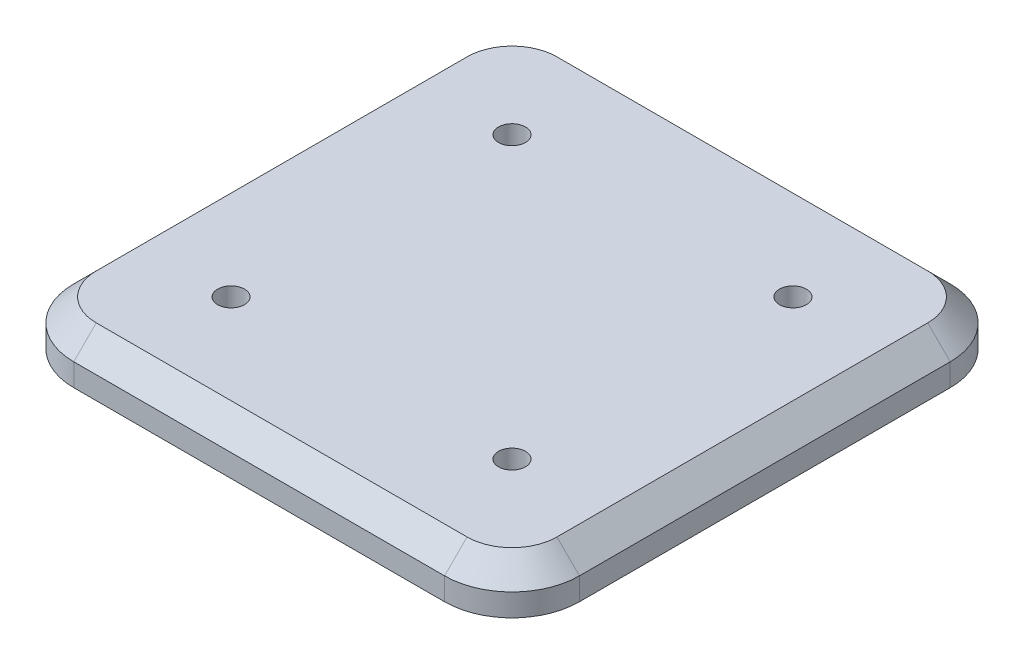
SolidWorks part; units mm, degrees
ref_plane "前基準面" through (0, 0, 0) normal (0, 0, 1) x (1, 0, 0)
ref_plane "上基準面" through (0, 0, 0) normal (0, 1, 0) x (1, 0, 0)
ref_plane "右基準面" through (0, 0, 0) normal (1, 0, 0) x (0, 0, -1)
ref_plane "平面1"
sketch "草圖1" plane through (0, 0, 0) normal (0, 1, 0) x (-1, 0, 0)
  line L0 (112.5, -112.5) -> (-112.5, -112.5)
  line L1 (-112.5, -112.5) -> (-112.5, 112.5)
  line L2 (-112.5, 112.5) -> (112.5, 112.5)
  line L3 (112.5, 112.5) -> (112.5, -112.5)
  dimension "D1" = 225
  dimension "D2" = 225
extrude "擠出1" add sketch "草圖1" along normal blind 20
fillet "圓角1" radius 30 4 edges at (-112.5, 10, 112.5) (-112.5, 10, -112.5) (112.5, 10, -112.5) (112.5, 10, 112.5)
chamfer "倒角1" distance 10 distance2 10 8 edges at (103.7132, 20, 103.7132) (0, 20, 112.5) (-103.7132, 20, 103.7132) (-112.5, 20, 0) (-103.7132, 20, -103.7132) (0, 20, -112.5) (103.7132, 20, -103.7132) (112.5, 20, 0)
hole_wizard "孔1" positions "草圖3" profile "草圖2" legacy
sketch "草圖3" plane through (0, 0, 0) normal (0, -1, 0) x (-1, 0, 0)
  point P1 (-87.5, 87.5)
  point P2 (-87.5, -87.5)
  point P3 (87.5, -87.5)
  point P4 (87.5, 87.5)
sketch "草圖2" plane through (87.5, 0, -87.5) normal (1, 0, 0) x (0, 0, -1)
  line L0 (0, 0) -> (0, 13.6052)
  line L1 (0, 13.6052) -> (6, 10)
  line L2 (6, 10) -> (6, 0)
  line L4 (6, 0) -> (0, 0)
  line L6 (0, 13.6052) -> (-6, 10) construction
  line L7 (0, -4.2442) -> (0, 117.3081) construction
  dimension "直徑" = 12
  dimension "深度" = 10
  dimension "導頭角度" = 118
hole_wizard "孔2" positions "草圖5" profile "草圖4" legacy
sketch "草圖5" plane through (0, 20, 0) normal (0, 1, 0) x (1, 0, 0)
  point P1 (-62.5, 62.5)
  point P2 (62.5, 62.5)
  point P3 (62.5, -62.5)
  point P4 (-62.5, -62.5)
sketch "草圖4" plane through (-62.5, 20, -62.5) normal (1, 0, 0) x (0, 0, 1)
  line L0 (0, 0) -> (0, 13.6052)
  line L1 (0, 13.6052) -> (6, 10)
  line L2 (6, 10) -> (6, 0)
  line L4 (6, 0) -> (0, 0)
  line L6 (0, 13.6052) -> (-6, 10) construction
  line L7 (0, -4.2442) -> (0, 117.3081) construction
  dimension "直徑" = 12
  dimension "深度" = 10
  dimension "導頭角度" = 118
